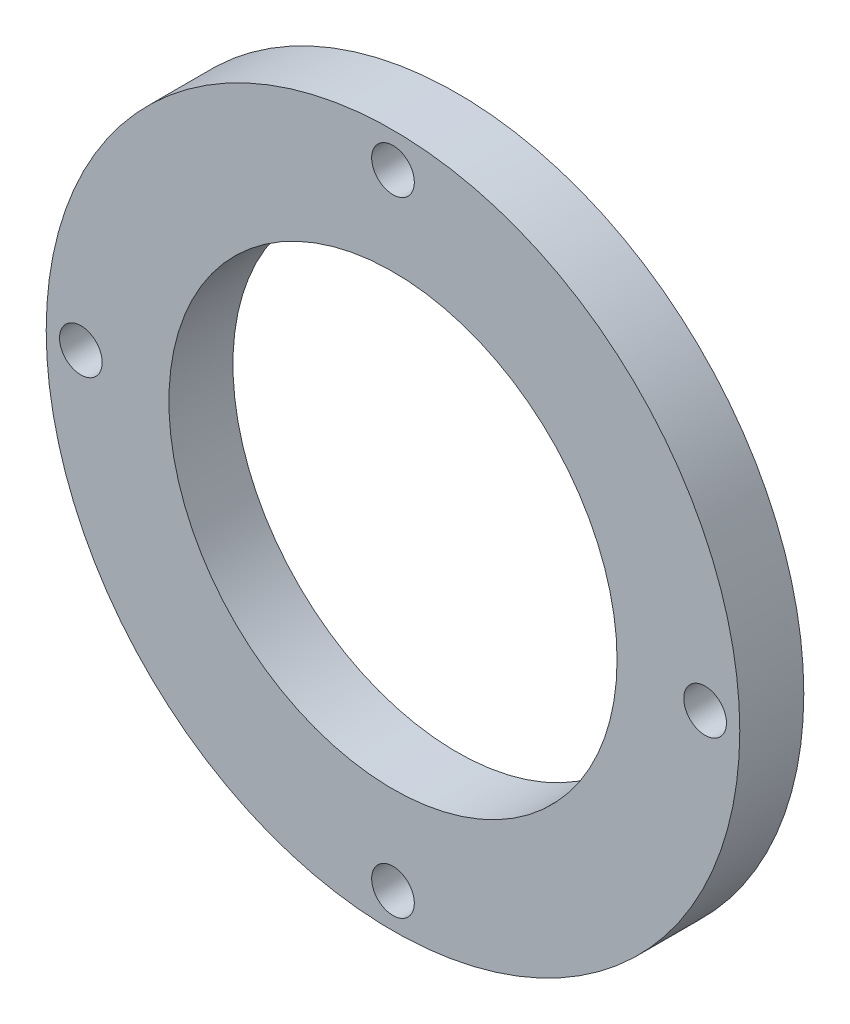
SolidWorks part; units mm, degrees
ref_plane "Plan de face" through (0, 0, 0) normal (0, 0, 1) x (1, 0, 0)
ref_plane "Plan de dessus" through (0, 0, 0) normal (0, 1, 0) x (1, 0, 0)
ref_plane "Plan de droite" through (0, 0, 0) normal (1, 0, 0) x (0, 0, -1)
sketch "Esquisse1" plane through (0, 0, 0) normal (0, 0, 1) x (1, 0, 0)
  circle A0 centre (0, 0) radius 21
  circle A1 centre (0, 0) radius 32.5
  circle A2 centre (0, 29.25) radius 2
  circle A3 centre (29.25, 0) radius 2
  circle A4 centre (0, -29.25) radius 2
  circle A5 centre (-29.25, 0) radius 2
  point P15 (0, 0)
  dimension "D1" = 65
  dimension "D2" = 42
  dimension "D3" = 4
  dimension "D5" = 29.25
  dimension "D4" = 4
extrude "Boss.-Extru.1" add sketch "Esquisse1" along normal blind 6
